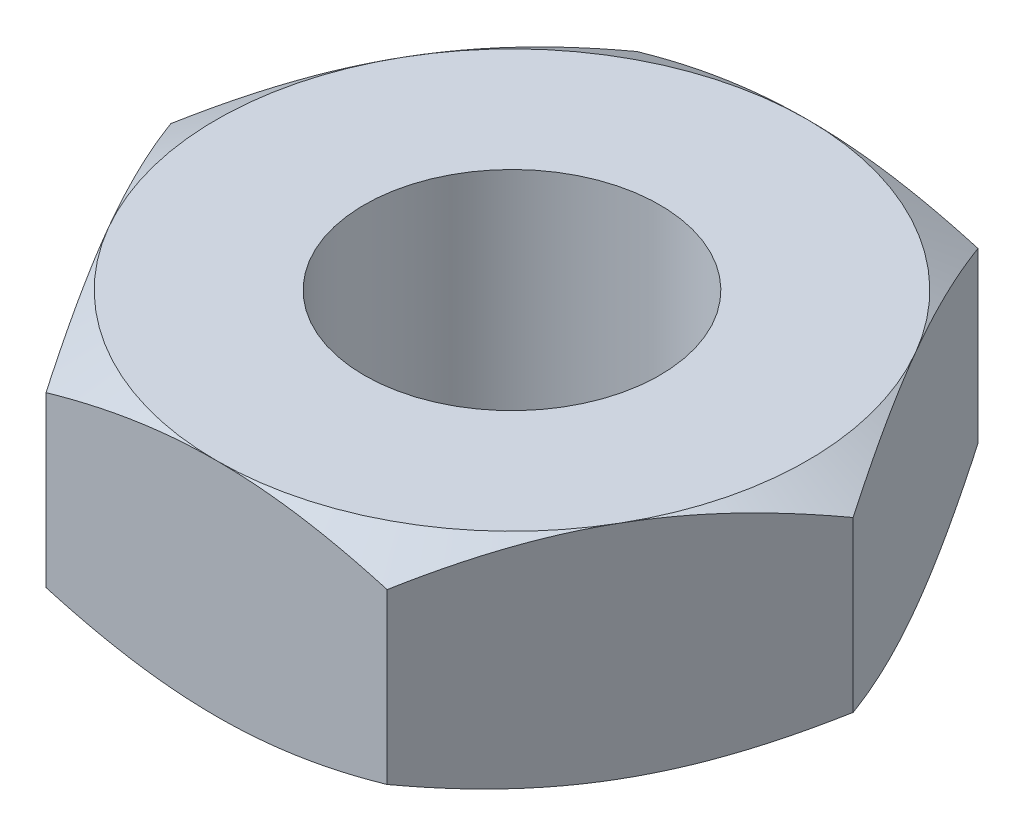
SolidWorks part; units mm, degrees
ref_plane "Front Plane" through (0, 0, 0) normal (0, 0, 1) x (1, 0, 0)
ref_plane "Top Plane" through (0, 0, 0) normal (0, 1, 0) x (1, 0, 0)
ref_plane "Right Plane" through (0, 0, 0) normal (1, 0, 0) x (0, 0, -1)
sketch "Sketch3" plane through (0, 0, 0) normal (0, 1, 0) x (1, 0, 0)
  line L1 (23.094, 0) -> (11.547, 20)
  line L2 (11.547, 20) -> (-11.547, 20)
  line L3 (-11.547, 20) -> (-23.094, 0)
  line L4 (-23.094, 0) -> (-11.547, -20)
  line L5 (-11.547, -20) -> (11.547, -20)
  line L6 (11.547, -20) -> (23.094, 0)
  circle A0 centre (0, 0) radius 10
  circle A1 centre (0, 0) radius 20 construction
  dimension "D1" = 40
  dimension "3" = 20
extrude "Boss-Extrude1" add sketch "Sketch3" along normal mid plane 15
sketch "Sketch4" plane through (0, -7.5, 0) normal (0, -1, 0) x (1, 0, 0)
  circle A0 centre (0, 0) radius 20
  dimension "D1" = 40
extrude "Cut-Extrude1" cut sketch "Sketch4" against normal blind 2 draft 60 flip side to cut
mirror "Mirror1" about plane through (0, 0, 0) normal (0, 1, 0) of "Cut-Extrude1"
